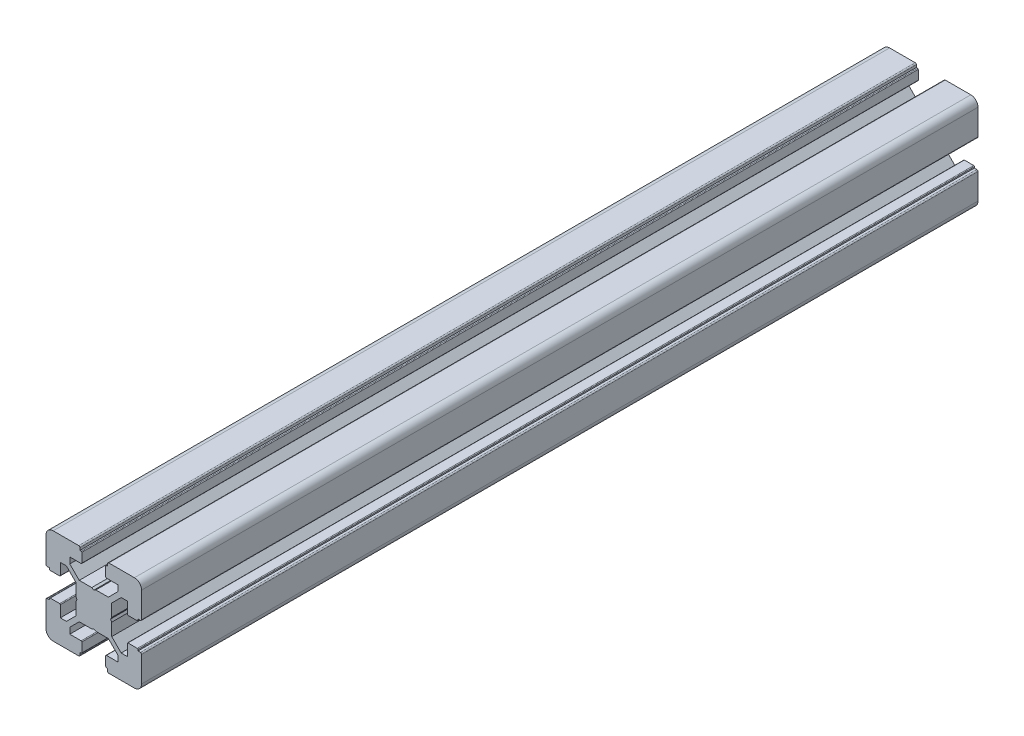
SolidWorks part; units mm, degrees
material "1060 Alloy"
ref_plane "Front Plane" through (0, 0, 0) normal (0, 0, 1) x (1, 0, 0)
ref_plane "Top Plane" through (0, 0, 0) normal (0, 1, 0) x (1, 0, 0)
ref_plane "Right Plane" through (0, 0, 0) normal (1, 0, 0) x (0, 0, -1)
sketch "Sketch2" plane through (0, 0, 0) normal (0, 0, 1) x (1, 0, 0)
  line L72 (-20.3, 9.9499) -> (-20.3, 14.7)
  line L73 (-20.6, 15) -> (-24.5, 15)
  line L74 (-24.8, 14.7) -> (-24.8, 14.2)
  line L75 (-24.8, 14.2) -> (-25.8, 14.2)
  line L76 (-26.3, 13.7) -> (-26.3, 3)
  line L77 (-23.3, 0) -> (-12.6, 0)
  line L78 (-12.1, 0.5) -> (-12.1, 1.5)
  line L79 (-12.1, 1.5) -> (-11.6, 1.5)
  line L80 (-11.3, 1.8) -> (-11.3, 5.7)
  line L81 (-11.6, 6) -> (-16.3501, 6)
  line L82 (-16.3501, 6) -> (-16.3501, 8.5356)
  line L83 (-16.3501, 8.5356) -> (-12.3856, 12.5001)
  line L84 (-12.3856, 12.5001) -> (-7.166, 12.5001)
  line L85 (-7.166, 12.5001) -> (-6.3, 13.0001)
  line L86 (-6.3, 13.0001) -> (-5.4339, 12.5001)
  line L87 (-5.4339, 12.5001) -> (-0.2143, 12.5001)
  line L88 (-0.2143, 12.5001) -> (3.7501, 8.5357)
  line L89 (3.7501, 8.5357) -> (3.7501, 6)
  line L90 (3.7501, 6) -> (-1, 6)
  line L91 (-1.3, 5.7) -> (-1.3, 1.8)
  line L92 (-1, 1.5) -> (-0.5, 1.5)
  line L93 (-0.5, 1.5) -> (-0.5, 0.5)
  line L94 (0, 0) -> (10.7, 0)
  line L95 (13.7, 3) -> (13.7, 13.7)
  line L96 (13.2, 14.2) -> (12.2, 14.2)
  line L97 (12.2, 14.2) -> (12.2, 14.7)
  line L98 (11.9, 15) -> (8, 15)
  line L99 (7.7, 14.7) -> (7.7, 9.9498)
  line L100 (7.7, 9.9498) -> (5.1644, 9.9498)
  line L101 (5.1644, 9.9498) -> (1.1999, 13.9143)
  line L102 (1.1999, 13.9143) -> (1.1999, 19.134)
  line L103 (1.1999, 19.134) -> (0.6999, 20)
  line L104 (0.6999, 20) -> (1.1999, 20.866)
  line L105 (1.1999, 20.866) -> (1.1999, 26.0857)
  line L106 (1.1999, 26.0857) -> (5.1643, 30.0501)
  line L107 (5.1643, 30.0501) -> (7.7, 30.0501)
  line L108 (7.7, 30.0501) -> (7.7, 25.3)
  line L109 (8, 25) -> (11.9, 25)
  line L110 (12.2, 25.3) -> (12.2, 25.8)
  line L111 (12.2, 25.8) -> (13.2, 25.8)
  line L112 (13.7, 26.3) -> (13.7, 37)
  line L113 (10.7, 40) -> (0.0001, 40)
  line L114 (-0.4999, 39.5) -> (-0.4999, 38.5)
  line L115 (-0.4999, 38.5) -> (-0.9999, 38.5)
  line L116 (-1.2999, 38.2) -> (-1.2999, 34.3)
  line L117 (-0.9999, 34) -> (3.7502, 34)
  line L118 (3.7502, 34) -> (3.7502, 31.4644)
  line L119 (3.7502, 31.4644) -> (-0.2143, 27.4999)
  line L120 (-0.2143, 27.4999) -> (-5.4339, 27.4999)
  line L121 (-5.4339, 27.4999) -> (-6.3, 26.9999)
  line L122 (-6.3, 26.9999) -> (-7.166, 27.4999)
  line L123 (-7.166, 27.4999) -> (-12.3856, 27.4999)
  line L124 (-12.3856, 27.4999) -> (-16.3501, 31.4643)
  line L125 (-16.3501, 31.4643) -> (-16.3501, 34)
  line L126 (-16.3501, 34) -> (-11.5999, 34)
  line L127 (-11.2999, 34.3) -> (-11.2999, 38.2)
  line L128 (-11.5999, 38.5) -> (-12.0999, 38.5)
  line L129 (-12.0999, 38.5) -> (-12.0999, 39.5)
  line L130 (-12.5999, 40) -> (-23.3, 40)
  line L131 (-26.3, 37) -> (-26.3, 26.3)
  line L132 (-25.8, 25.8) -> (-24.8, 25.8)
  line L133 (-24.8, 25.8) -> (-24.8, 25.3)
  line L134 (-24.5, 25) -> (-20.6, 25)
  line L135 (-20.3, 25.3) -> (-20.3, 30.0502)
  line L136 (-20.3, 30.0502) -> (-17.7643, 30.0502)
  line L137 (-17.7643, 30.0502) -> (-13.7999, 26.0857)
  line L138 (-13.7999, 26.0857) -> (-13.7999, 20.866)
  line L139 (-13.7999, 20.866) -> (-13.2999, 20)
  line L140 (-13.2999, 20) -> (-13.7999, 19.134)
  line L141 (-13.7999, 19.134) -> (-13.7999, 13.9143)
  line L142 (-13.7999, 13.9143) -> (-17.7643, 9.9499)
  line L143 (-17.7643, 9.9499) -> (-20.3, 9.9499)
  line L144 (-20.3, 9.9499) -> (-20.3, 14.7)
  line L145 (-20.6, 15) -> (-24.5, 15)
  line L146 (-24.8, 14.7) -> (-24.8, 14.2)
  line L147 (-24.8, 14.2) -> (-25.8, 14.2)
  line L148 (-26.3, 13.7) -> (-26.3, 3)
  line L149 (-23.3, 0) -> (-12.6, 0)
  line L150 (-12.1, 0.5) -> (-12.1, 1.5)
  line L151 (-12.1, 1.5) -> (-11.6, 1.5)
  line L152 (-11.3, 1.8) -> (-11.3, 5.7)
  line L153 (-11.6, 6) -> (-16.3501, 6)
  line L154 (-16.3501, 6) -> (-16.3501, 8.5356)
  line L155 (-16.3501, 8.5356) -> (-12.3856, 12.5001)
  line L156 (-12.3856, 12.5001) -> (-7.166, 12.5001)
  line L157 (-7.166, 12.5001) -> (-6.3, 13.0001)
  line L158 (-6.3, 13.0001) -> (-5.4339, 12.5001)
  line L159 (-5.4339, 12.5001) -> (-0.2143, 12.5001)
  line L160 (-0.2143, 12.5001) -> (3.7501, 8.5357)
  line L161 (3.7501, 8.5357) -> (3.7501, 6)
  line L162 (3.7501, 6) -> (-1, 6)
  line L163 (-1.3, 5.7) -> (-1.3, 1.8)
  line L164 (-1, 1.5) -> (-0.5, 1.5)
  line L165 (-0.5, 1.5) -> (-0.5, 0.5)
  line L166 (0, 0) -> (10.7, 0)
  line L167 (13.7, 3) -> (13.7, 13.7)
  line L168 (13.2, 14.2) -> (12.2, 14.2)
  line L169 (12.2, 14.2) -> (12.2, 14.7)
  line L170 (11.9, 15) -> (8, 15)
  line L171 (7.7, 14.7) -> (7.7, 9.9498)
  line L172 (7.7, 9.9498) -> (5.1644, 9.9498)
  line L173 (5.1644, 9.9498) -> (1.1999, 13.9143)
  line L174 (1.1999, 13.9143) -> (1.1999, 19.134)
  line L175 (1.1999, 19.134) -> (0.6999, 20)
  line L176 (0.6999, 20) -> (1.1999, 20.866)
  line L177 (1.1999, 20.866) -> (1.1999, 26.0857)
  line L178 (1.1999, 26.0857) -> (5.1643, 30.0501)
  line L179 (5.1643, 30.0501) -> (7.7, 30.0501)
  line L180 (7.7, 30.0501) -> (7.7, 25.3)
  line L181 (8, 25) -> (11.9, 25)
  line L182 (12.2, 25.3) -> (12.2, 25.8)
  line L183 (12.2, 25.8) -> (13.2, 25.8)
  line L184 (13.7, 26.3) -> (13.7, 37)
  line L185 (10.7, 40) -> (0.0001, 40)
  line L186 (-0.4999, 39.5) -> (-0.4999, 38.5)
  line L187 (-0.4999, 38.5) -> (-0.9999, 38.5)
  line L188 (-1.2999, 38.2) -> (-1.2999, 34.3)
  line L189 (-0.9999, 34) -> (3.7502, 34)
  line L190 (3.7502, 34) -> (3.7502, 31.4644)
  line L191 (3.7502, 31.4644) -> (-0.2143, 27.4999)
  line L192 (-0.2143, 27.4999) -> (-5.4339, 27.4999)
  line L193 (-5.4339, 27.4999) -> (-6.3, 26.9999)
  line L194 (-6.3, 26.9999) -> (-7.166, 27.4999)
  line L195 (-7.166, 27.4999) -> (-12.3856, 27.4999)
  line L196 (-12.3856, 27.4999) -> (-16.3501, 31.4643)
  line L197 (-16.3501, 31.4643) -> (-16.3501, 34)
  line L198 (-16.3501, 34) -> (-11.5999, 34)
  line L199 (-11.2999, 34.3) -> (-11.2999, 38.2)
  line L200 (-11.5999, 38.5) -> (-12.0999, 38.5)
  line L201 (-12.0999, 38.5) -> (-12.0999, 39.5)
  line L202 (-12.5999, 40) -> (-23.3, 40)
  line L203 (-26.3, 37) -> (-26.3, 26.3)
  line L204 (-25.8, 25.8) -> (-24.8, 25.8)
  line L205 (-24.8, 25.8) -> (-24.8, 25.3)
  line L206 (-24.5, 25) -> (-20.6, 25)
  line L207 (-20.3, 25.3) -> (-20.3, 30.0502)
  line L208 (-20.3, 30.0502) -> (-17.7643, 30.0502)
  line L209 (-17.7643, 30.0502) -> (-13.7999, 26.0857)
  line L210 (-13.7999, 26.0857) -> (-13.7999, 20.866)
  line L211 (-13.7999, 20.866) -> (-13.2999, 20)
  line L212 (-13.2999, 20) -> (-13.7999, 19.134)
  line L213 (-13.7999, 19.134) -> (-13.7999, 13.9143)
  line L214 (-13.7999, 13.9143) -> (-17.7643, 9.9499)
  line L215 (-17.7643, 9.9499) -> (-20.3, 9.9499)
  arc A28 (-20.3, 14.7) -> (-20.6, 15) centre (-20.6, 14.7) ccw
  arc A29 (-24.5, 15) -> (-24.8, 14.7) centre (-24.5, 14.7) ccw
  arc A30 (-25.8, 14.2) -> (-26.3, 13.7) centre (-25.8, 13.7) ccw
  arc A31 (-26.3, 3) -> (-23.3, 0) centre (-23.3, 3) ccw
  arc A32 (-12.6, 0) -> (-12.1, 0.5) centre (-12.6, 0.5) ccw
  arc A33 (-11.6, 1.5) -> (-11.3, 1.8) centre (-11.6, 1.8) ccw
  arc A34 (-11.3, 5.7) -> (-11.6, 6) centre (-11.6, 5.7) ccw
  arc A35 (-1, 6) -> (-1.3, 5.7) centre (-1, 5.7) ccw
  arc A36 (-1.3, 1.8) -> (-1, 1.5) centre (-1, 1.8) ccw
  arc A37 (-0.5, 0.5) -> (0, 0) centre (0, 0.5) ccw
  arc A38 (10.7, 0) -> (13.7, 3) centre (10.7, 3) ccw
  arc A39 (13.7, 13.7) -> (13.2, 14.2) centre (13.2, 13.7) ccw
  arc A40 (12.2, 14.7) -> (11.9, 15) centre (11.9, 14.7) ccw
  arc A41 (8, 15) -> (7.7, 14.7) centre (8, 14.7) ccw
  arc A42 (7.7, 25.3) -> (8, 25) centre (8, 25.3) ccw
  arc A43 (11.9, 25) -> (12.2, 25.3) centre (11.9, 25.3) ccw
  arc A44 (13.2, 25.8) -> (13.7, 26.3) centre (13.2, 26.3) ccw
  arc A45 (13.7, 37) -> (10.7, 40) centre (10.7, 37) ccw
  arc A46 (0.0001, 40) -> (-0.4999, 39.5) centre (0.0001, 39.5) ccw
  arc A47 (-0.9999, 38.5) -> (-1.2999, 38.2) centre (-0.9999, 38.2) ccw
  arc A48 (-1.2999, 34.3) -> (-0.9999, 34) centre (-0.9999, 34.3) ccw
  arc A49 (-11.5999, 34) -> (-11.2999, 34.3) centre (-11.5999, 34.3) ccw
  arc A50 (-11.2999, 38.2) -> (-11.5999, 38.5) centre (-11.5999, 38.2) ccw
  arc A51 (-12.0999, 39.5) -> (-12.5999, 40) centre (-12.5999, 39.5) ccw
  arc A52 (-23.3, 40) -> (-26.3, 37) centre (-23.3, 37) ccw
  arc A53 (-26.3, 26.3) -> (-25.8, 25.8) centre (-25.8, 26.3) ccw
  arc A54 (-24.8, 25.3) -> (-24.5, 25) centre (-24.5, 25.3) ccw
  arc A55 (-20.6, 25) -> (-20.3, 25.3) centre (-20.6, 25.3) ccw
  arc A56 (-20.3, 14.7) -> (-20.6, 15) centre (-20.6, 14.7) ccw
  arc A57 (-24.5, 15) -> (-24.8, 14.7) centre (-24.5, 14.7) ccw
  arc A58 (-25.8, 14.2) -> (-26.3, 13.7) centre (-25.8, 13.7) ccw
  arc A59 (-26.3, 3) -> (-23.3, 0) centre (-23.3, 3) ccw
  arc A60 (-12.6, 0) -> (-12.1, 0.5) centre (-12.6, 0.5) ccw
  arc A61 (-11.6, 1.5) -> (-11.3, 1.8) centre (-11.6, 1.8) ccw
  arc A62 (-11.3, 5.7) -> (-11.6, 6) centre (-11.6, 5.7) ccw
  arc A63 (-1, 6) -> (-1.3, 5.7) centre (-1, 5.7) ccw
  arc A64 (-1.3, 1.8) -> (-1, 1.5) centre (-1, 1.8) ccw
  arc A65 (-0.5, 0.5) -> (0, 0) centre (0, 0.5) ccw
  arc A66 (10.7, 0) -> (13.7, 3) centre (10.7, 3) ccw
  arc A67 (13.7, 13.7) -> (13.2, 14.2) centre (13.2, 13.7) ccw
  arc A68 (12.2, 14.7) -> (11.9, 15) centre (11.9, 14.7) ccw
  arc A69 (8, 15) -> (7.7, 14.7) centre (8, 14.7) ccw
  arc A70 (7.7, 25.3) -> (8, 25) centre (8, 25.3) ccw
  arc A71 (11.9, 25) -> (12.2, 25.3) centre (11.9, 25.3) ccw
  arc A72 (13.2, 25.8) -> (13.7, 26.3) centre (13.2, 26.3) ccw
  arc A73 (13.7, 37) -> (10.7, 40) centre (10.7, 37) ccw
  arc A74 (0.0001, 40) -> (-0.4999, 39.5) centre (0.0001, 39.5) ccw
  arc A75 (-0.9999, 38.5) -> (-1.2999, 38.2) centre (-0.9999, 38.2) ccw
  arc A76 (-1.2999, 34.3) -> (-0.9999, 34) centre (-0.9999, 34.3) ccw
  arc A77 (-11.5999, 34) -> (-11.2999, 34.3) centre (-11.5999, 34.3) ccw
  arc A78 (-11.2999, 38.2) -> (-11.5999, 38.5) centre (-11.5999, 38.2) ccw
  arc A79 (-12.0999, 39.5) -> (-12.5999, 40) centre (-12.5999, 39.5) ccw
  arc A80 (-23.3, 40) -> (-26.3, 37) centre (-23.3, 37) ccw
  arc A81 (-26.3, 26.3) -> (-25.8, 25.8) centre (-25.8, 26.3) ccw
  arc A82 (-24.8, 25.3) -> (-24.5, 25) centre (-24.5, 25.3) ccw
  arc A83 (-20.6, 25) -> (-20.3, 25.3) centre (-20.6, 25.3) ccw
  dimension "D1" = 0
extrude "Boss-Extrude1" add sketch "Sketch2" along normal blind 350 contours L185 A74 L186 L187 A75 L188 A76 L189 L190 L191 L192 L193 L194 L195 L196 L197 L198 A77 L199 A78 L200 L201 A79 L202 A80 L203 A81 L204 L205 A82 L206 A83 L207 L208 L209 L210 L211 L212 L213 L214 L215 L144 A56 L145 A57 L146 L147 A58 L148 A59 L149 A60 L150 L151 A61 L152 A62 L153 L154 L155 L156 L157 L158 L159 L160 L161 L162 A63 L163 A64 L164 L165 A65 L166 A66 L167 A67 L168 L169 A68 L170 A69 L171 L172 L173 L174 L175 L176 L177 L178 L179 L180 A70 L181 A71 L182 L183 A72 L184 A73
